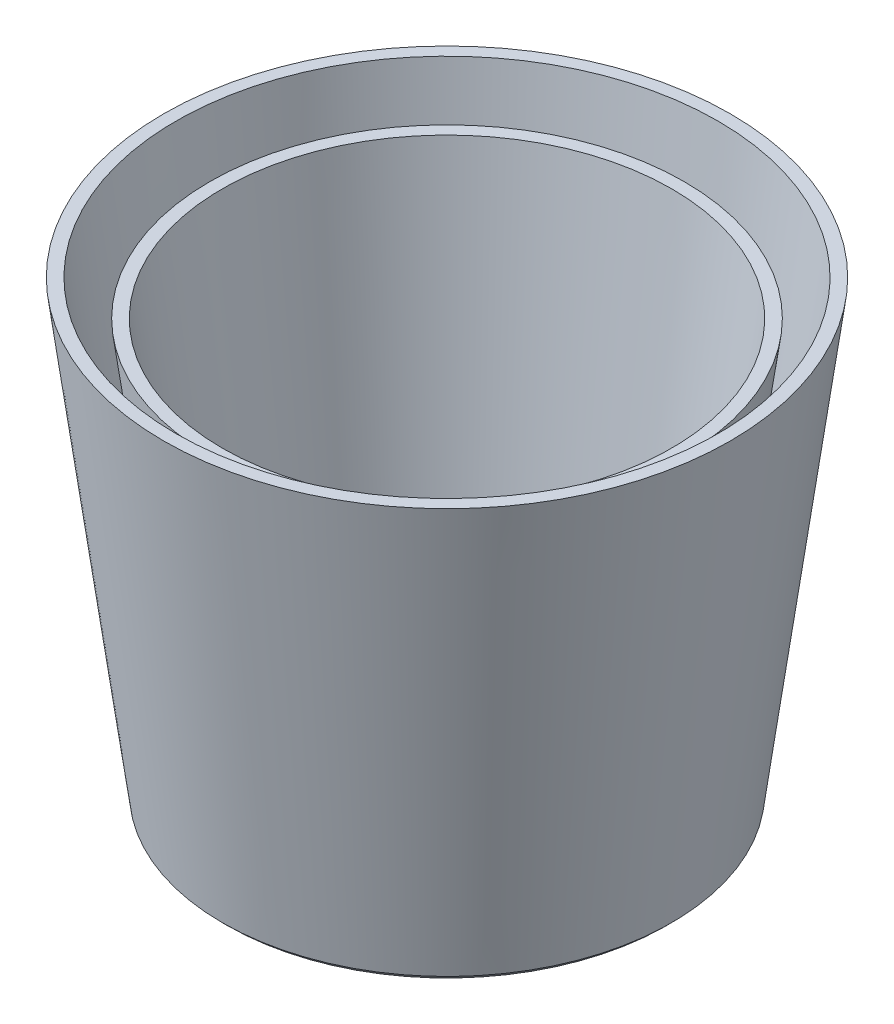
SolidWorks part; units mm, degrees
ref_plane "Front Plane" through (0, 0, 0) normal (0, 0, 1) x (1, 0, 0)
ref_plane "Top Plane" through (0, 0, 0) normal (0, 1, 0) x (1, 0, 0)
ref_plane "Right Plane" through (0, 0, 0) normal (1, 0, 0) x (0, 0, -1)
sketch "Sketch1" plane through (0, 0, 0) normal (1, 0, 0) x (0, 0, -1)
  line L0 (0, 0) -> (52.5, 0) construction
  line L1 (0, 0) -> (0, -95) construction
  line L2 (0, -95) -> (40, -95)
  line L3 (51.5789, -7) -> (40, -95)
  line L5 (54.6048, -7) -> (42.6311, -98)
  line L6 (0, -98) -> (42.6311, -98)
  line L10 (0, 3) -> (55.9206, 3) construction
  line L11 (55.9206, 3) -> (42.6311, -98) construction
  line L12 (0, -105) -> (48.7704, -105)
  line L13 (62.5862, 0) -> (48.7704, -105)
  line L14 (0, -108) -> (51.4015, -108)
  line L15 (65.4404, -1.3045) -> (51.4015, -108)
  line L16 (0, -98) -> (0, -105)
  line L18 (62.4145, -1.3045) -> (48.7704, -105) construction
  line L21 (65.8292, 1.6507) -> (65.4404, -1.3045)
  line L22 (0, -95) -> (-3, -95)
  line L23 (-3, -95) -> (-3, -108)
  line L24 (-3, -108) -> (0, -108)
  line L26 (62.5862, 0) -> (62.8034, 1.6507)
  line L27 (62.8034, 1.6507) -> (65.8292, 1.6507)
  line L28 (51.5789, -7) -> (54.6048, -7)
  line L29 (52.5, 0) -> (40, -95) construction
  line L30 (55.5259, 0) -> (42.6311, -98) construction
  dimension "D1" = 52.5
  dimension "D2" = 40
  dimension "D3" = 95
  dimension "D6" = 62.8034
  dimension "D7" = 3
  dimension "D8" = 7
  dimension "D9" = 65.4404
  dimension "D4" = 3
  dimension "D5" = 10
revolve "Revolve2" add sketch "Sketch1" angle 360 about L23
sketch "Sketch2" plane through (0, -108, 0) normal (0, -1, 0) x (1, 0, 0)
  circle A0 centre (0, 35) radius 5
  dimension "D2" = 10
  dimension "D1" = 35
extrude "Boss-Extrude1" add sketch "Sketch2" against normal up to surface (13 mm away) up to face at (0, -95, 46)
fillet "Fillet3" radius 3 2 edges at (0, -105, 30) (0, -98, 40)
pattern_circular "CirPattern2" count 5 over 360 about axis through (0, 0, 3) along (0, 1, 0) of "Fillet3", "Boss-Extrude1"
sketch "Sketch3" plane through (0, -95, 0) normal (0, 1, 0) x (1, 0, 0)
  circle A0 centre (0, -3.1615) radius 4
  dimension "D1" = 8
  dimension "D2" = 3.1615
extrude "Cut-Extrude1" cut sketch "Sketch3" against normal up to surface (10 mm away) up to face at (-30.4338, -105, 4.8885)
sketch "Sketch4" plane through (0, -95, 0) normal (0, 1, 0) x (1, 0, 0)
  circle A0 centre (0, 30) radius 2.5
  dimension "D1" = 5
  dimension "D2" = 30
extrude "Cut-Extrude2" cut sketch "Sketch4" against normal up to surface (10 mm away) up to face at (-30.4338, -105, 4.8885)
pattern_circular "CirPattern3" count 5 over 360 about axis through (0, 0, 3) along (0, 1, 0) of "Cut-Extrude2"
fillet "Fillet4" radius 3 1 edges at (0, -95, 46)
chamfer "Chamfer2" distance 1 angle 45 1 edges at (0, -108, 57.4015)
